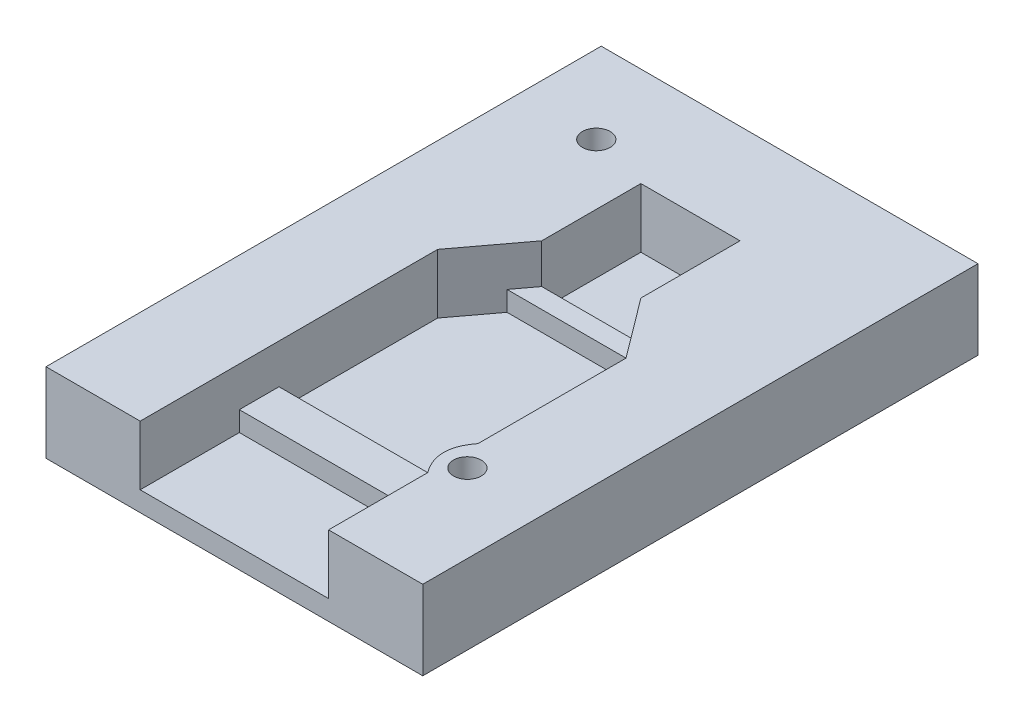
SolidWorks part; units mm, degrees
ref_plane "Front Plane" through (0, 0, 0) normal (0, 0, 1) x (1, 0, 0)
ref_plane "Top Plane" through (0, 0, 0) normal (0, 1, 0) x (1, 0, 0)
ref_plane "Right Plane" through (0, 0, 0) normal (1, 0, 0) x (0, 0, -1)
sketch "Sketch1" plane through (0, 0, 0) normal (0, 1, 0) x (1, 0, 0)
  line L1 (0, 0) -> (13.5, 0)
  line L2 (0, 0) -> (0, 20)
  line L3 (0, 20) -> (13.5, 20)
  line L4 (13.5, 0) -> (13.5, 20)
  dimension "D1" = 20
  dimension "D2" = 13.5
extrude "Boss-Extrude1" add sketch "Sketch1" along normal blind 1
sketch "Sketch2" plane through (0, 1, 0) normal (0, 1, 0) x (1, 0, 0)
  line L0 (2, 10) -> (2, 2)
  line L1 (0, 20) -> (13.5, 20)
  line L2 (0, 20) -> (0, 0)
  line L3 (0, 0) -> (2, 0)
  line L4 (13.5, 20) -> (13.5, 0)
  line L5 (4.25, 13) -> (2, 10)
  line L6 (4.25, 18) -> (4.25, 13)
  line L7 (2, 2) -> (2, 0)
  line L8 (9.25, 18) -> (9.25, 13)
  line L10 (11.5, 10) -> (11.5, 2.5356)
  line L11 (4.25, 18) -> (9.25, 18)
  line L12 (2, 18) -> (11.5, 18) construction
  line L13 (9.25, 13) -> (11.5, 10)
  line L14 (2, 18) -> (2, 2) construction
  line L15 (2, 2) -> (11.5, 2) construction
  line L16 (11.5, 18) -> (11.5, 2) construction
  line L17 (11.5, 0) -> (13.5, 0)
  line L19 (0, 0) -> (13.5, 0) construction
  spline S0 degree 2 poles (11.5, 2.5356) (10.5366, 1.3002) (11.5, 0) knots 0 0 0 1 1 1
  dimension "D1" = 5
  dimension "D2" = 5
  dimension "D4" = 4.25
  dimension "D5" = 4.25
  dimension "D6" = 2
extrude "Boss-Extrude2" add sketch "Sketch2" along normal blind 3
sketch "Sketch3" plane through (0, 1, 0) normal (0, 1, 0) x (1, 0, 0)
  line L0 (4.25, 13) -> (9.25, 13)
  line L1 (9.25, 13) -> (10, 12)
  line L2 (9.25, 13) -> (11.5, 10) construction
  line L3 (10, 12) -> (3.5, 12)
  line L4 (2, 10) -> (4.25, 13) construction
  line L5 (3.5, 12) -> (4.25, 13)
  line L6 (13.5, 20) -> (0, 20) construction
  line L7 (13.5, 0) -> (13.5, 20) construction
  line L8 (0, 20) -> (0, 0) construction
  dimension "D1" = 1
  dimension "D2" = 7
  dimension "D3" = 4.25
  dimension "D4" = 3.5
extrude "Boss-Extrude3" add sketch "Sketch3" along normal blind 1
sketch "Sketch4" plane through (0, 0, 0) normal (0, -1, 0) x (1, 0, 0)
  line L0 (0, -20) -> (0, 0) construction
  line L1 (13.5, -20) -> (0, -20) construction
  line L2 (0, 0) -> (13.5, 0) construction
  line L3 (13.5, 0) -> (13.5, -20) construction
  circle A0 centre (1.2, -18.8) radius 0.7
  circle A1 centre (12.3, -1.2) radius 0.7
  dimension "D1" = 1.2
  dimension "D2" = 1.2
  dimension "D3" = 1.2
  dimension "D4" = 1.2
extrude "Cut-Extrude1" cut sketch "Sketch4" against normal blind 11.5 from offset 1 offset against normal yes
sketch "Sketch5" plane through (0, 1, 0) normal (0, 1, 0) x (1, 0, 0)
  line L0 (11.5, 10) -> (11.5, 2.5356) construction
  line L1 (2, 0) -> (11.5, 0)
  line L2 (2, 0) -> (2, 2)
  line L3 (2, 2) -> (11.5, 2)
  line L4 (11.5, 0) -> (11.5, 2)
  dimension "D1" = 2
extrude "Boss-Extrude4" add sketch "Sketch5" along normal blind 1
sketch "Sketch6" plane through (0, 1, 0) normal (0, 1, 0) x (1, 0, 0)
  line L1 (0, 20) -> (13.5, 20)
  line L2 (0, 20) -> (0, 0)
  line L3 (0, 0) -> (13.5, 0)
  line L4 (13.5, 20) -> (13.5, 0)
  line L5 (-2.75, 23) -> (16.25, 23)
  line L6 (-2.75, 23) -> (-2.75, -5)
  line L7 (-2.75, -5) -> (16.25, -5)
  line L8 (16.25, 23) -> (16.25, -5)
  dimension "D1" = 2.75
  dimension "D2" = 2.75
  dimension "D3" = 3
  dimension "D4" = 5
  dimension "D5" = 19
extrude "Boss-Extrude5" add sketch "Sketch6" against normal blind 1
sketch "Sketch7" plane through (0, 4, 0) normal (0, 1, 0) x (1, 0, 0)
  line L0 (2, 0) -> (2, -5)
  line L1 (0, 20) -> (13.5, 20)
  line L2 (0, 20) -> (0, 0)
  line L3 (0, 0) -> (2, 0)
  line L4 (13.5, 20) -> (13.5, 0)
  line L5 (-2.75, 23) -> (16.25, 23)
  line L6 (-2.75, 23) -> (-2.75, -5)
  line L7 (-2.75, -5) -> (2, -5)
  line L8 (16.25, 23) -> (16.25, -5)
  line L9 (11.5, 0) -> (11.5, -5)
  line L10 (11.5, 0) -> (13.5, 0)
  line L11 (11.5, -5) -> (16.25, -5)
extrude "Boss-Extrude6" add sketch "Sketch7" against normal up to surface (3 mm away) up to face at (6.75, 1, -10)
